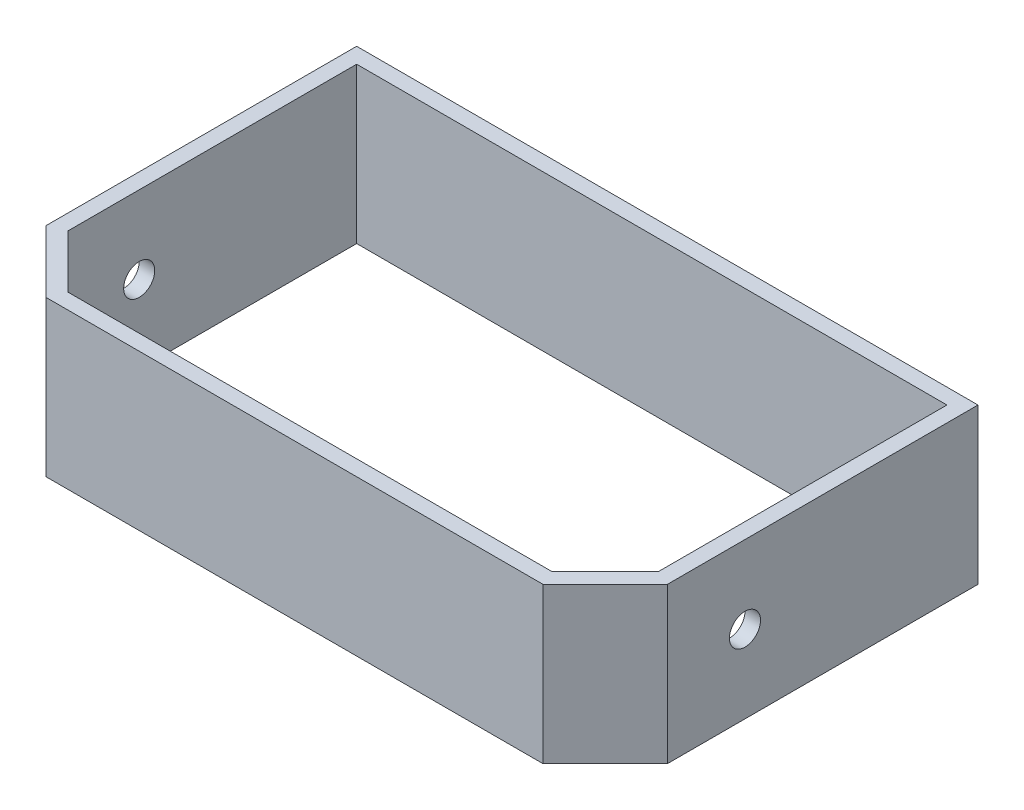
SolidWorks part; units mm, degrees
ref_plane "Front Plane" through (0, 0, 0) normal (0, 0, 1) x (1, 0, 0)
ref_plane "Top Plane" through (0, 0, 0) normal (0, 1, 0) x (1, 0, 0)
ref_plane "Right Plane" through (0, 0, 0) normal (1, 0, 0) x (0, 0, -1)
sketch "Sketch1" plane through (0, 0, 0) normal (0, 1, 0) x (1, 0, 0)
  line L0 (-50.8, 0) -> (50.8, 0)
  line L1 (50.8, 0) -> (63.5, 12.7)
  line L2 (63.5, 12.7) -> (63.5, 76.2)
  line L3 (63.5, 76.2) -> (-63.5, 76.2)
  line L4 (0, 76.2) -> (0, 0) construction
  line L5 (-50.8, 0) -> (-63.5, 12.7)
  line L6 (-63.5, 12.7) -> (-63.5, 76.2)
  line L7 (60.325, 73.025) -> (-60.325, 73.025)
  line L8 (-60.325, 14.0151) -> (-60.325, 73.025)
  line L9 (-49.4849, 3.175) -> (-60.325, 14.0151)
  line L10 (-49.4849, 3.175) -> (49.4849, 3.175)
  line L11 (49.4849, 3.175) -> (60.325, 14.0151)
  line L12 (60.325, 14.0151) -> (60.325, 73.025)
  point P4 (0, 0)
  dimension "D1" = 135
  dimension "D2" = 76.2
  dimension "D3" = 101.6
  dimension "D4" = 127
  dimension "D5" = 3.175
extrude "Boss-Extrude1" add sketch "Sketch1" along normal mid plane 31.75
sketch "Sketch2" plane through (-63.5, 0, 0) normal (-1, 0, 0) x (0, 0, 1)
  line L0 (-28.575, 15.875) -> (-28.575, -15.875) construction
  line L1 (-76.2, 15.875) -> (-12.7, 15.875) construction
  line L2 (-76.2, -15.875) -> (-12.7, -15.875) construction
  line L3 (-12.7, 15.875) -> (-12.7, -15.875) construction
  circle A0 centre (-28.575, 0) radius 3.175
  dimension "D1" = 6.35
  dimension "D2" = 15.875
extrude "Cut-Extrude1" cut sketch "Sketch2" against normal up to next
sketch "Sketch3" plane through (63.5, 0, 0) normal (1, 0, 0) x (0, 0, -1)
  circle A0 centre (28.575, 0) radius 3.175 construction
  circle A1 centre (28.575, 0) radius 3.175
extrude "Cut-Extrude2" cut sketch "Sketch3" against normal up to next
